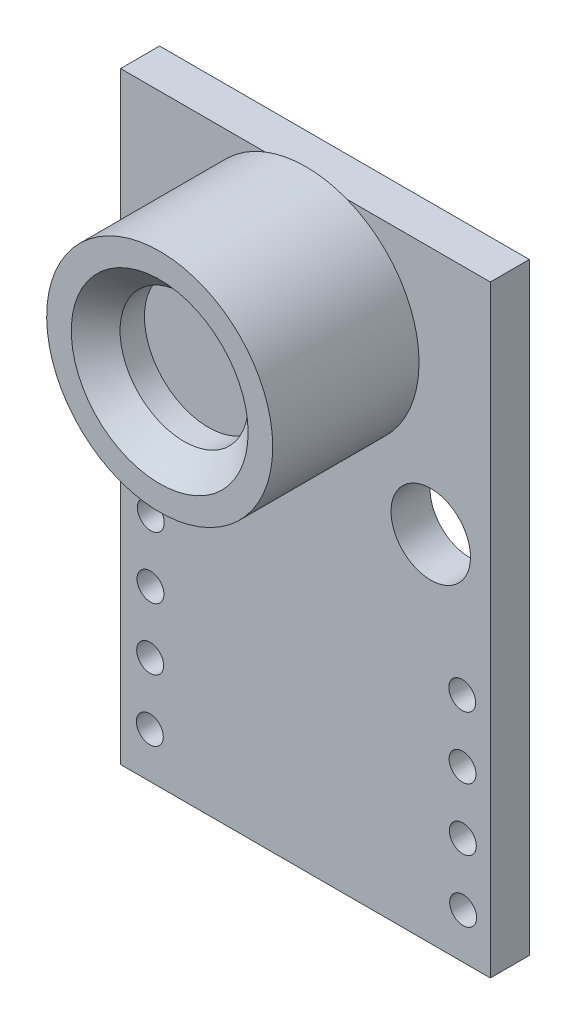
SolidWorks part; units mm, degrees
ref_plane "Plan de face" through (0, 0, 0) normal (0, 0, 1) x (1, 0, 0)
ref_plane "Plan de dessus" through (0, 0, 0) normal (0, 1, 0) x (1, 0, 0)
ref_plane "Plan de droite" through (0, 0, 0) normal (1, 0, 0) x (0, 0, -1)
sketch "Esquisse1" plane through (0, 0, 0) normal (0, 0, 1) x (1, 0, 0)
  line L0 (0.2983, 193.8546) -> (15.4983, 193.8546) construction
  line L1 (7.8896, 183.5505) -> (7.8896, 168.7008) construction
  line L2 (0.265, 193.9996) -> (15.428, 193.9996)
  line L3 (0.265, 193.9996) -> (0.265, 169.2815)
  line L4 (0.265, 169.2815) -> (15.428, 169.2815)
  line L5 (15.428, 193.9996) -> (15.428, 169.2815)
  circle A0 centre (2.7401, 183.8607) radius 1.6204
  circle A1 centre (12.9858, 183.8196) radius 1.6292
  circle A2 centre (1.5035, 178.7574) radius 0.5518
  circle A3 centre (1.4908, 176.2175) radius 0.5518
  circle A4 centre (1.4781, 173.6775) radius 0.5518
  circle A5 centre (1.4655, 171.1375) radius 0.5518
  circle A6 centre (14.3138, 171.1375) radius 0.5518
  circle A7 centre (14.3011, 173.6775) radius 0.5518
  circle A8 centre (14.2884, 176.2175) radius 0.5518
  circle A9 centre (14.2758, 178.7574) radius 0.5518
  dimension "D1" = 15.2
  dimension "D2" = 4
sketch "Esquisse2" plane through (0, 0, 0) normal (0, 0, 1) x (1, 0, 0)
  circle A0 centre (7.87, 189.6801) radius 4.6353
extrude "Boss.-Extru.1" add sketch "Esquisse1" against normal blind 1.6
extrude "Boss.-Extru.2" add sketch "Esquisse2" along normal blind 6
sketch "Esquisse3" plane through (0, 0, 6) normal (0, 0, 1) x (1, 0, 0)
  circle A0 centre (7.87, 189.6801) radius 2.6258
extrude "Enlèv. mat.-Extru.1" cut sketch "Esquisse3" against normal blind 2
chamfer "Chanfrein1" distance 1 angle 45 1 edges at (10.4958, 189.6801, 6)
